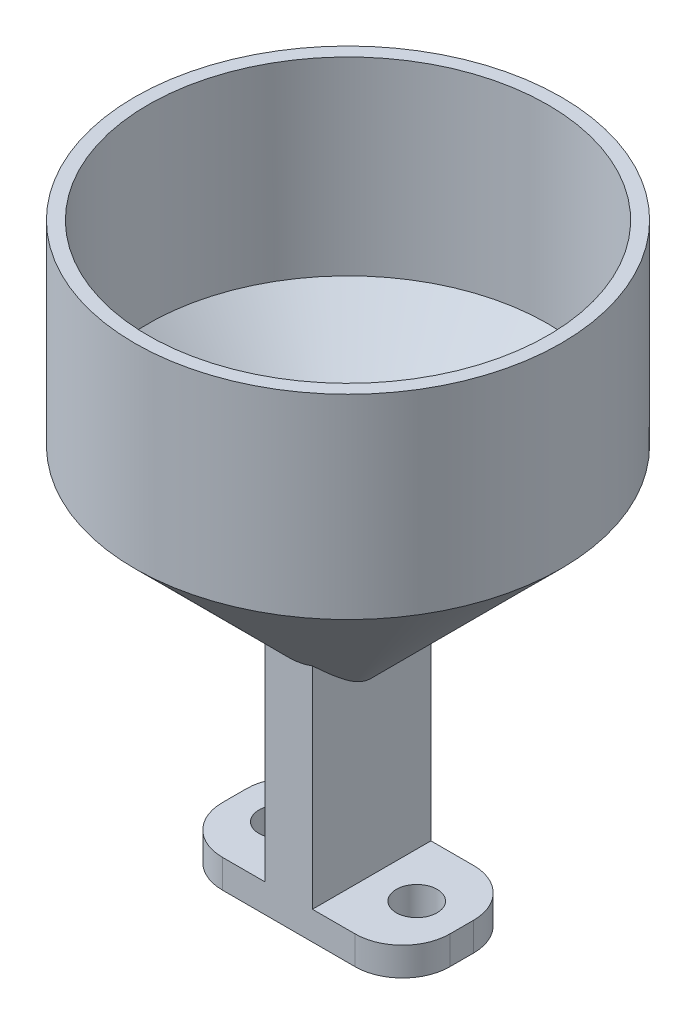
SolidWorks part; units mm, degrees
material "ABS"
ref_plane "Front Plane" through (0, 0, 0) normal (0, 0, 1) x (1, 0, 0)
ref_plane "Top Plane" through (0, 0, 0) normal (0, 1, 0) x (1, 0, 0)
ref_plane "Right Plane" through (0, 0, 0) normal (1, 0, 0) x (0, 0, -1)
sketch "Sketch1" plane through (0, 0, 0) normal (0, 1, 0) x (1, 0, 0)
  line L0 (-7.25, 0) -> (7.25, 0) construction
  line L2 (-2.5, -6.25) -> (2.5, -6.25) construction
  line L3 (-2.5, -6.25) -> (-2.5, 6.25) construction
  line L4 (-2.5, 6.25) -> (2.5, 6.25) construction
  line L5 (2.5, -6.25) -> (2.5, 6.25) construction
  line L6 (-2.5, -6.25) -> (2.5, 6.25) construction
  line L7 (-2.5, 6.25) -> (2.5, -6.25) construction
  line L8 (-7, -6.25) -> (7, -6.25)
  line L9 (-12, -1.25) -> (-12, 1.25)
  line L10 (-7, 6.25) -> (7, 6.25)
  line L11 (12, -1.25) -> (12, 1.25)
  line L12 (-12, -6.25) -> (12, 6.25) construction
  line L13 (-12, 6.25) -> (12, -6.25) construction
  circle A0 centre (-7.25, 0) radius 2.15
  circle A1 centre (7.25, 0) radius 2.15
  circle A2 centre (-7.25, 0) radius 4.75 construction
  circle A3 centre (7.25, 0) radius 4.75 construction
  arc A4 (-7, -6.25) -> (-12, -1.25) centre (-7, -1.25) cw
  arc A5 (7, -6.25) -> (12, -1.25) centre (7, -1.25) ccw
  arc A6 (7, 6.25) -> (12, 1.25) centre (7, 1.25) cw
  arc A7 (-12, 1.25) -> (-7, 6.25) centre (-7, 1.25) cw
  point P4 (0, 0)
  point P9 (0, 0)
  point P14 (0, 0)
  dimension "D1" = 4.3
  dimension "D3" = 9.5
  dimension "D5" = 5
  dimension "D2" = 14.5
  dimension "D4" = 12.5
extrude "Boss-Extrude1" add sketch "Sketch1" along normal mid plane 3
sketch "Sketch3" plane through (0, 0, 6.25) normal (0, 0, 1) x (1, 0, 0)
  line L0 (-7, 1.5) -> (7, 1.5) construction
  line L1 (-2.5, 21.5) -> (2.5, 21.5) construction
  line L2 (-2.5, 21.5) -> (-2.5, 1.5) construction
  line L3 (-2.5, 1.5) -> (2.5, 1.5) construction
  line L4 (2.5, 21.5) -> (2.5, 1.5) construction
  line L5 (-2.5, 21.5) -> (2.5, 1.5) construction
  line L6 (-2.5, 1.5) -> (2.5, 21.5) construction
  line L8 (-12, 1.5) -> (-12, -1.5) construction
  line L9 (-2.5, 1.5) -> (-12, 1.5) construction
  line L10 (-2.5, 21.5) -> (2.5, 21.5)
  line L11 (-4.5, 17) -> (-12, 17) construction
  line L12 (-4.5, 17) -> (-4.5, 21.5) construction
  line L13 (-4.5, 21.5) -> (-12, 21.5) construction
  line L14 (-12, 17) -> (-12, 21.5) construction
  line L15 (-4.5, 17) -> (-12, 21.5) construction
  line L16 (-4.5, 21.5) -> (-12, 17) construction
  line L17 (-2.5, 1.5) -> (-2.5, 21.5)
  line L18 (-2.5, 1.5) -> (-12, 1.5) construction
  line L19 (-2.5, 1.5) -> (-2.5, 6.5) construction
  line L20 (-2.5, 6.5) -> (-12, 6.5) construction
  line L21 (-12, 1.5) -> (-12, 6.5) construction
  line L22 (-2.5, 1.5) -> (-12, 6.5) construction
  line L23 (-2.5, 6.5) -> (-12, 1.5) construction
  line L24 (0, 0) -> (0, 32.0144) construction
  line L25 (2.5, 21.5) -> (2.5, 1.5)
  line L26 (2.5, 1.5) -> (-2.5, 1.5)
  point P0 (0, 11.5)
  point P7 (-8.25, 19.25)
  point P11 (-7.25, 4)
  point P13 (0, 21.5)
  point P19 (-7.25, 1.5)
  dimension "D1" = 9.5
  dimension "D2" = 20
  dimension "D3" = 7.5
  dimension "D4" = 4.5
  dimension "D5" = 5
extrude "Boss-Extrude3" add sketch "Sketch3" against normal up to surface (12.5 mm away) up to face at (0, 0, -6.25)
sketch "Sketch4" plane through (0, 0, 0) normal (0, 0, 1) x (1, 0, 0)
  line L0 (-2.5, 19.5) -> (-22.5, 39.5)
  line L1 (-2.5, 1.5) -> (-2.5, 21.5) construction
  line L4 (-21.0858, 40.0858) -> (-22.0858, 39.0858) construction
  line L7 (-2.5, 21.5) -> (0, 21.5)
  line L8 (0, -200000) -> (0, 200032.0144) construction
  line L9 (-2.5, 19.5) -> (0, 19.5)
  line L11 (0, 0) -> (0, 34.2554) construction
  line L12 (-22.5, 39.5) -> (-22.5, 60.0858)
  line L13 (-22.5, 60.0858) -> (-21.0858, 60.0858)
  line L14 (-21.0858, 60.0858) -> (-21.0858, 40.0858)
  line L15 (-21.0858, 40.0858) -> (-2.5, 21.5)
  line L16 (0, 21.5) -> (0, 19.5)
  dimension "D1" = 45
  dimension "D2" = 45
  dimension "D4" = 20
revolve "Revolve1" add sketch "Sketch4" angle 360 about L11
sketch "Sketch5" plane through (0, 21.5, 0) normal (0, 1, 0) x (1, 0, 0)
  line L6 (2.5, -6.25) -> (2.5, -3.7417)
  line L7 (-2.5, -3.7417) -> (-2.5, -6.25)
  line L8 (-2.5, -6.25) -> (2.5, -6.25)
  line L9 (2.5, -6.25) -> (2.5, -3.7417)
  line L10 (-2.5, -3.7417) -> (-2.5, -6.25)
  line L11 (-2.5, -6.25) -> (2.5, -6.25)
  line L15 (-2.5, 6.25) -> (-2.5, 3.7417)
  line L16 (2.5, 3.7417) -> (2.5, 6.25)
  line L17 (2.5, 6.25) -> (-2.5, 6.25)
  line L18 (-2.5, 6.25) -> (-2.5, 3.7417)
  line L19 (2.5, 3.7417) -> (2.5, 6.25)
  line L20 (2.5, 6.25) -> (-2.5, 6.25)
  arc A2 (-2.5, -3.7417) -> (2.5, -3.7417) centre (0, 0) ccw
  arc A3 (-2.5, -3.7417) -> (2.5, -3.7417) centre (0, 0) ccw
  arc A5 (2.5, 3.7417) -> (-2.5, 3.7417) centre (0, 0) ccw
  arc A6 (2.5, 3.7417) -> (-2.5, 3.7417) centre (0, 0) ccw
  dimension "D1" = 0
  dimension "D2" = 0
extrude "Boss-Extrude4" add sketch "Sketch5" along normal up to next
